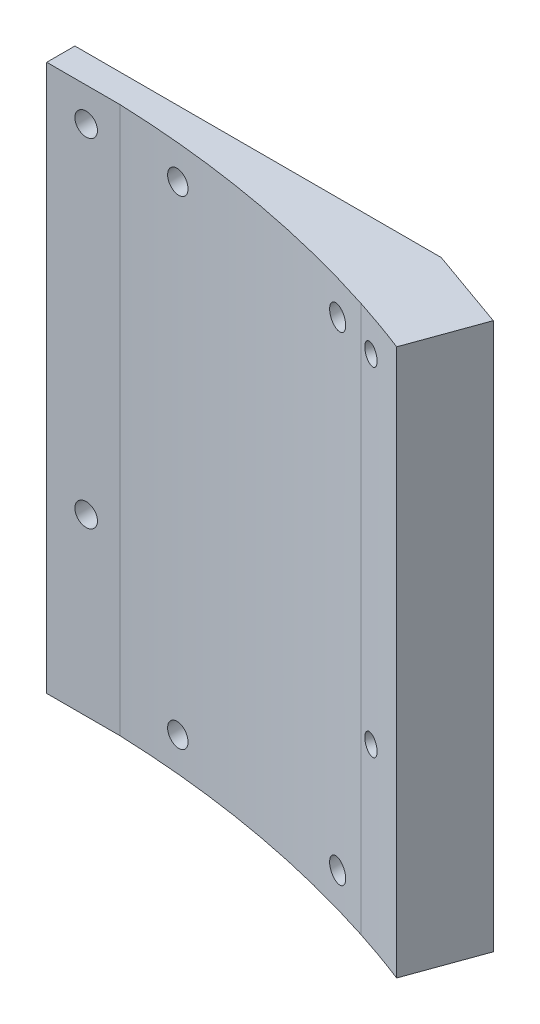
SolidWorks part; units mm, degrees
ref_plane "Front Plane" through (0, 0, 0) normal (0, 0, 1) x (1, 0, 0)
ref_plane "Top Plane" through (0, 0, 0) normal (0, 1, 0) x (1, 0, 0)
ref_plane "Right Plane" through (0, 0, 0) normal (1, 0, 0) x (0, 0, -1)
sketch "Sketch2" plane through (0, 0, 0) normal (0, 1, 0) x (1, 0, 0)
  line L0 (-120, 144.0703) -> (120, 144.0703) construction
  line L2 (6, 187.5) -> (58, 187.5) construction
  line L3 (58, 187.5) -> (58, 302.5) construction
  line L8 (58, 302.5) -> (0, 302.5) construction
  line L9 (0, 302.5) -> (0, 228.1791) construction
  line L10 (0, 228.1791) -> (58, 228.1791) construction
  line L11 (0, 144.0703) -> (0, 334.8408) construction
  line L32 (7.4972, 192.5) -> (58, 192.5)
  line L34 (7.4972, 192.5) -> (-7, 192.5)
  line L35 (-7, 192.5) -> (-7, 187.5)
  line L36 (-7, 187.5) -> (6, 187.5)
  line L37 (62.7337, 176.6939) -> (67.1159, 189.0366) construction
  line L38 (58, 192.5) -> (72.1308, 187.483)
  line L39 (62.7337, 176.6939) -> (53.0987, 180.0309) construction
  line L40 (72.3298, 187.411) -> (67.7777, 174.8211)
  line L41 (72.1308, 187.483) -> (72.3298, 187.411)
  arc A0 (120, 144.0703) -> (-116.9975, 146.5191) centre (0, 0) ccw construction
  spline S1 degree 2 poles (6, 187.5) (32.6742, 186.4915) (58, 178.3038) knots 0 0 0 1 1 1
  spline S2 degree 2 poles (58, 178.3038) (62.9372, 176.6978) (67.7777, 174.8211) knots 0 0 0 1 1 1
  dimension "D1" = 375
  dimension "D2" = 240
  dimension "D3" = 52
  dimension "D4" = 115
  dimension "D5" = 58
  dimension "D17" = 90
  dimension "D18" = 5
  dimension "D19" = 7
  dimension "D20" = 5
  dimension "D21" = 5.25
extrude "Boss-Extrude1" add sketch "Sketch2" along normal blind 120
sketch "Sketch7" plane through (0, 0, -192.5) normal (0, 0, -1) x (-1, 0, 0)
  line L0 (-58, 120) -> (-58, 0) construction
  line L1 (-7.4972, 0) -> (-58, 0) construction
  line L2 (-58, 48.5) -> (-23.134, 48.5) construction
  line L3 (-58, 97) -> (7, 97)
  line L4 (7, 120) -> (7, 0) construction
  line L5 (7, 97) -> (7, 120)
  line L6 (7, 120) -> (-58, 120)
  line L7 (-58, 120) -> (-58, 97)
  circle A0 centre (-17, 6) radius 2
  circle A1 centre (-52, 6) radius 2
  circle A2 centre (-17, 91) radius 2
  circle A3 centre (-52, 91) radius 2
  circle A4 centre (0, 31) radius 2
  circle A5 centre (0, 91) radius 2
  dimension "D1" = 4
  dimension "D2" = 4
  dimension "D9" = 4
  dimension "D10" = 4
  dimension "D15" = 97
  dimension "D3" = 35
  dimension "D4" = 6
  dimension "D5" = 6
  dimension "D6" = 6
  dimension "D7" = 42.5
  dimension "D8" = 6
  dimension "D11" = 60
  dimension "D12" = 7
  dimension "D13" = 6
  dimension "D14" = 7
extrude "Cut-Extrude3" cut sketch "Sketch7" against normal blind 20
sketch "Sketch8" plane through (67.1874, 0, -189.2381) normal (0.3346, 0, -0.9424) x (-0.9424, 0, -0.3346)
  line L1 (2.2493, 91) -> (2.2493, 31) construction
  line L2 (9.7493, 97) -> (9.7493, 0) construction
  line L3 (9.7493, 97) -> (-5.2456, 97)
  line L4 (-5.2456, 120) -> (-5.2456, 0) construction
  line L6 (-5.2456, 120) -> (9.7493, 120)
  line L7 (9.7493, 120) -> (9.7493, 97)
  line L8 (-5.2456, 120) -> (-14.1393, 120)
  line L9 (-14.1393, 120) -> (-14.1393, 97)
  line L10 (-14.1393, 97) -> (-5.2456, 97)
  circle A0 centre (2.2493, 31) radius 1.75
  circle A1 centre (2.2493, 91) radius 1.75
  dimension "D1" = 3.5
  dimension "D3" = 3.5
  dimension "D2" = 6
  dimension "D4" = 60
  dimension "D5" = 7.5
extrude "Cut-Extrude4" cut sketch "Sketch8" against normal blind 20
